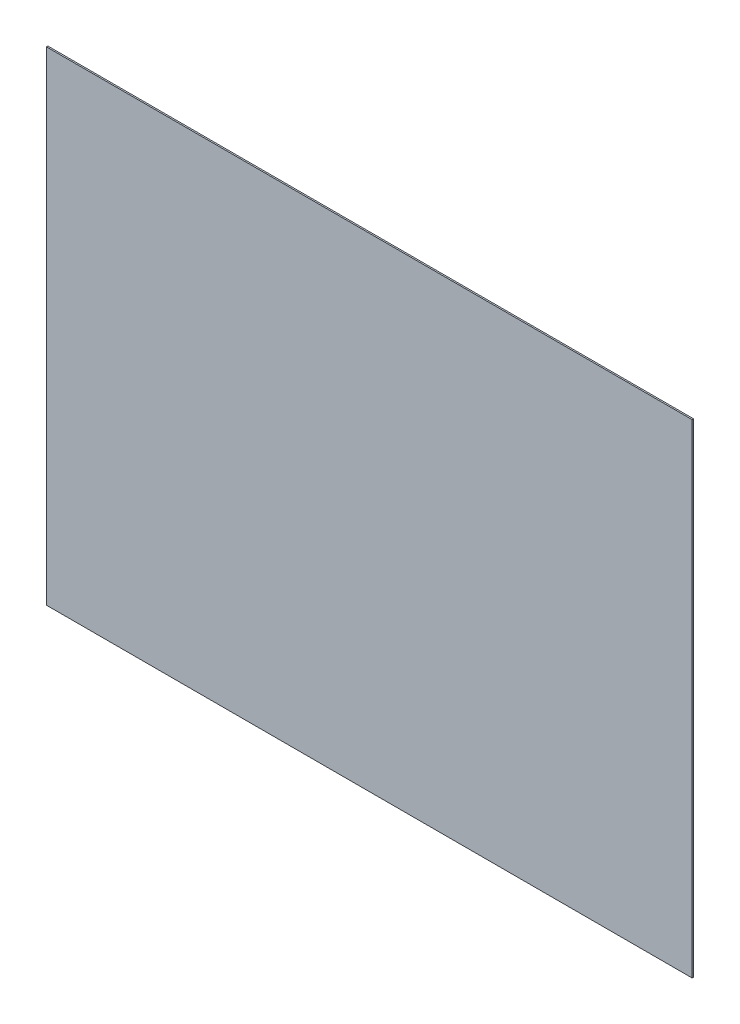
SolidWorks part; units mm, degrees
material "1345 Alloy"
ref_plane "Front Plane" through (0, 0, 0) normal (0, 0, 1) x (1, 0, 0)
ref_plane "Top Plane" through (0, 0, 0) normal (0, 1, 0) x (1, 0, 0)
ref_plane "Right Plane" through (0, 0, 0) normal (1, 0, 0) x (0, 0, -1)
sketch "Sketch1" plane through (0, 0, 0) normal (0, 0, 1) x (1, 0, 0)
  line L1 (-225, 168.5) -> (225, 168.5)
  line L2 (-225, 168.5) -> (-225, -168.5)
  line L3 (-225, -168.5) -> (225, -168.5)
  line L4 (225, 168.5) -> (225, -168.5)
  line L5 (-225, 168.5) -> (225, -168.5) construction
  line L6 (-225, -168.5) -> (225, 168.5) construction
  point P0 (0, 0)
  dimension "D1" = 450
  dimension "D2" = 337
extrude "Boss-Extrude1" add sketch "Sketch1" along normal blind 1
